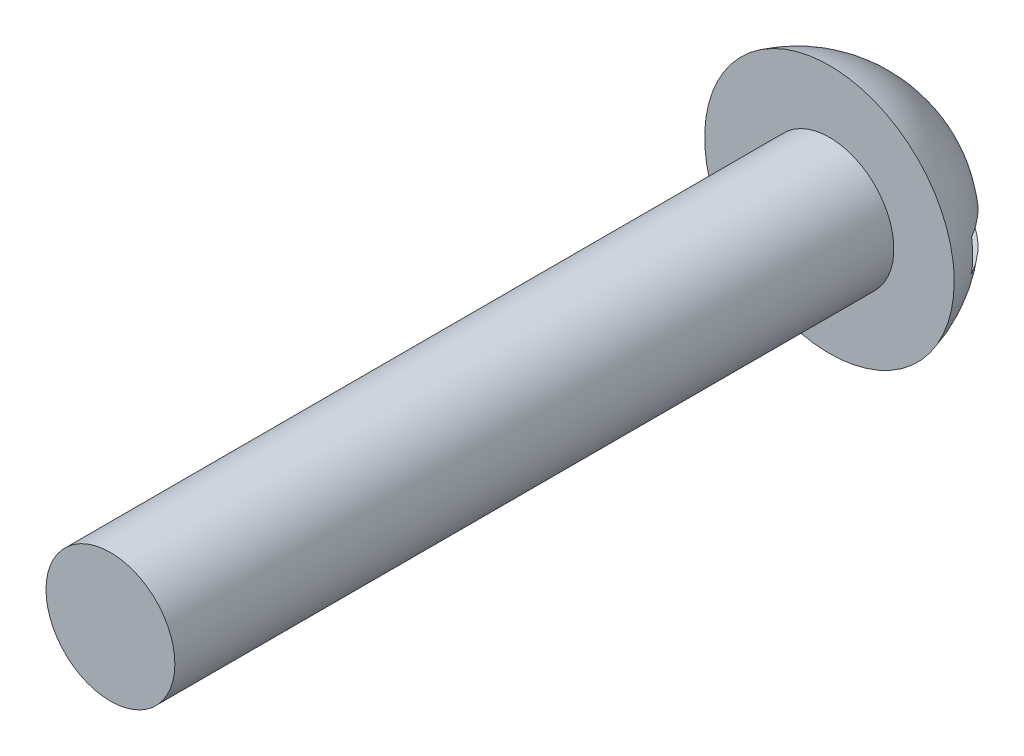
SolidWorks part; units mm, degrees
revolve "Base-Revolve" add sketch "Sketch1" angle 360 about L1
sketch "Sketch1" plane through (0, 0, 0) normal (1, 0, 0) x (0, 0, -1)
  line L0 (-22.86, 15.2822) -> (-20.7264, 15.2822)
  line L1 (-28.5941, 15.2822) -> (6.9659, 15.2822) construction
  line L2 (-22.86, 18.0366) -> (-22.86, 15.2822)
  arc A0 (-20.7264, 15.2822) -> (-22.86, 18.0366) centre (-23.5712, 15.2822) ccw
  dimension "D2" = 2.8448
  dimension "D1" = 2.1336
ref_plane "Plane1" through (0, 0, 0) normal (0, 0, 1) x (1, 0, 0)
ref_plane "Plane2" through (0, 0, 0) normal (0, 1, 0) x (1, 0, 0)
ref_plane "Plane3" through (0, 0, 0) normal (1, 0, 0) x (0, 0, -1)
sketch "Sketch2" plane through (0, 0, 22.86) normal (0, 0, 1) x (1, 0, 0)
  circle A0 centre (0, 15.24) radius 1.4224
  dimension "D1" = 2.8448
extrude "Boss-Extrude1" add sketch "Sketch2" along normal blind 15.875
cosmetic thread "Cosmetic Thread1" parameters "D1"=15.875, "D2"=2.2606
sketch "Sketch4" plane through (0, 0, 0) normal (1, 0, 0) x (0, 0, -1)
  line L2 (-22.1711, 14.9266) -> (-20.7487, 14.9266)
  line L3 (-22.1711, 15.6378) -> (-20.7487, 15.6378)
  line L4 (-22.1711, 15.6378) -> (-22.1711, 14.9266)
  arc A1 (-22.86, 12.5277) -> (-22.86, 18.0366) centre (-23.5712, 15.2822) ccw construction
  arc A2 (-20.7487, 14.9266) -> (-20.7487, 15.6378) centre (-23.5712, 15.2822) ccw
  dimension "D2" = 0.7112
  dimension "D1" = 1.4224
  dimension "D3" = 0.3556
extrude "Cut-Extrude1" cut sketch "Sketch4" against normal through all
mirror "Mirror1" about plane through (0, 15.2822, 23.5712) normal (1, 0, 0) of "Cut-Extrude1"
equation "\"D1@Sketch1\"=(3/4)*\"D1@Sketch2\""
equation "\"D2@Sketch1\"=\"D1@Sketch2\""
equation "\"D1@Sketch4\"=.5*\"D1@Sketch2\""
equation "\"D2@Sketch4\"=.25*\"D1@Sketch2\""
equation "\"D3@Sketch4\"=(1/8)*\"D1@Sketch2\""
